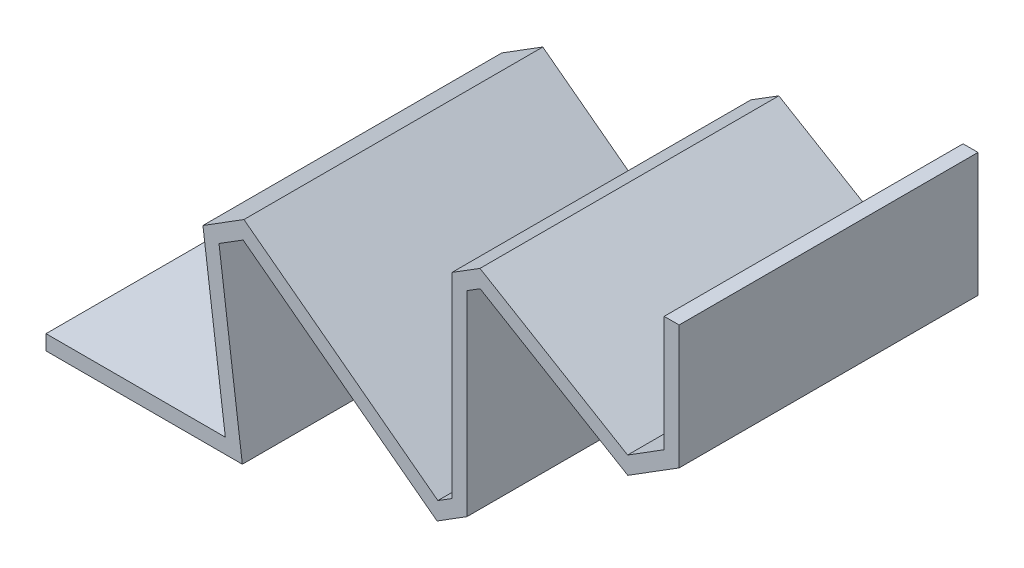
SolidWorks part; units mm, degrees
material "PBT General Purpose"
ref_plane "Front Plane" through (0, 0, 0) normal (0, 0, 1) x (1, 0, 0)
ref_plane "Top Plane" through (0, 0, 0) normal (0, 1, 0) x (1, 0, 0)
ref_plane "Right Plane" through (0, 0, 0) normal (1, 0, 0) x (0, 0, -1)
sketch "frame_outline" plane through (0, 0, 0) normal (0, 0, 1) x (1, 0, 0)
  line L123 (0, 0) -> (0, 0.25)
  line L124 (0, 0) -> (3, 0)
  line L136 (0, 0.25) -> (3, 0.25)
  line L137 (3, 0.25) -> (2.6255, 3.1301)
  line L138 (2.6255, 3.1301) -> (3.3111, 3.5586)
  line L139 (3.3111, 3.5586) -> (6.5556, 1.1099)
  line L140 (6.5556, 1.1099) -> (6.7922, 1.2577)
  line L141 (6.7922, 1.2577) -> (6.7922, 4.5332)
  line L142 (6.7922, 4.5332) -> (7.2598, 4.8254)
  line L143 (7.2598, 4.8254) -> (9.7295, 3.3563)
  line L144 (9.7295, 3.3563) -> (10.3416, 3.7388)
  line L145 (10.3416, 3.7388) -> (10.3416, 5.6715)
  line L146 (10.3416, 5.6715) -> (10.5916, 5.6715)
  line L147 (10.5916, 5.6715) -> (10.5916, 3.6002)
  line L148 (10.5916, 3.6002) -> (9.7327, 3.0635)
  line L149 (9.7327, 3.0635) -> (7.263, 4.5326)
  line L150 (7.263, 4.5326) -> (7.0422, 4.3947)
  line L151 (7.0422, 4.3947) -> (7.0422, 1.1191)
  line L152 (7.0422, 1.1191) -> (6.5423, 0.8067)
  line L153 (6.5423, 0.8067) -> (3.2978, 3.2554)
  line L155 (3.2846, 0) -> (3, 0)
  line L156 (3.2978, 3.2554) -> (2.8941, 3.0032)
  line L157 (2.8941, 3.0032) -> (3.2846, 0)
  point P13 (7.2338, 4.5481)
  point P16 (7.0422, 4.3947)
  dimension "D1" = 0.25
  dimension "D2" = 3
  dimension "D3" = 0.25
  dimension "D4" = 0.25
  dimension "D5" = 0.25
  dimension "D6" = 0.25
  dimension "D7" = 0.25
  dimension "D8" = 0.25
  dimension "D9" = 0.25
  dimension "D10" = 0.25
  dimension "D11" = 0.25
extrude "Boss-Extrude1" add sketch "frame_outline" along normal mid plane 5
equation "\"t\"= 0.25'thickness of the sheets"
equation "\"t_cf\"= 0.115'thickness of single carbon fiber layer"
equation "\"t_kapton\"= 0.025'thickness of single Kapton flex layer"
equation "\"t_fr4\"= 0.1'thickness of FR4 with copper layer"
equation "\"joint_flex\"= 0.1'Width of flextures gap"
equation "\"joint_flex_eff\"= 0.02'Width of flecture after castelation"
equation "\"joint_fold\"= 0.2'Width of folding joints for 90deg fold"
equation "\"gap_tolerance\"= 0.002'Width to have interfecence fit between carbon fiber inserts"
equation "\"assemble_angle\"= 90'Angle of assembly parts"
equation "\"D1@Boss-Extrude1\"=\"t\""
equation "\"link_lift\"= 0.5'Actuation linkage amplification for the lift motion"
equation "\"link_swing\"= 0.45'Actuation linkage amplification for the swing motion"
